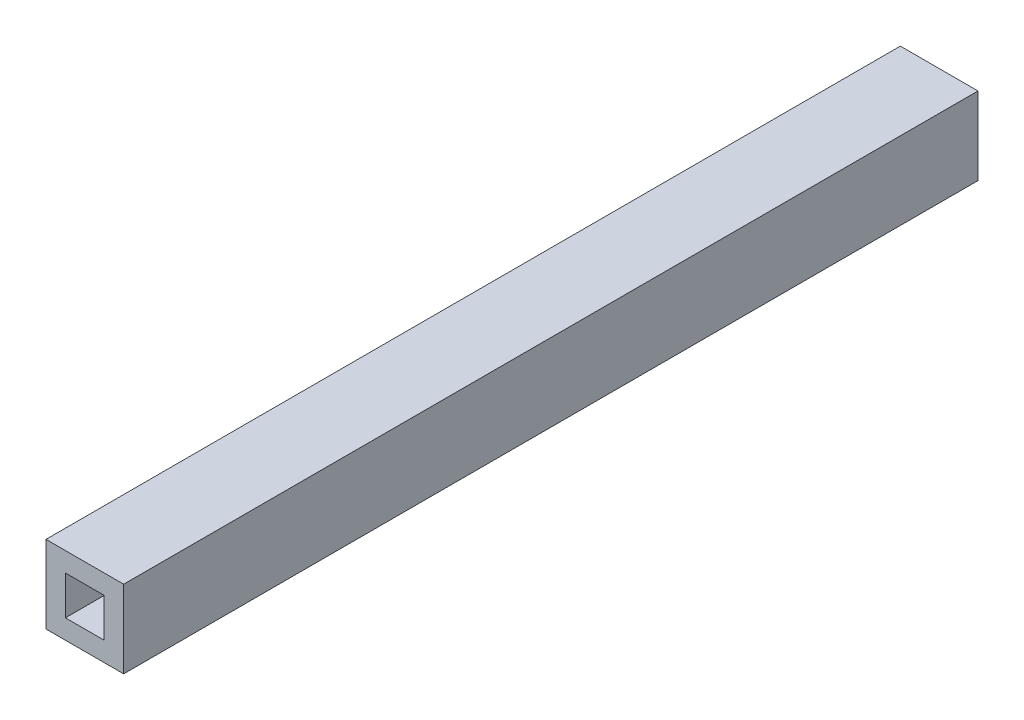
SolidWorks part; units mm, degrees
material "6063-O"
ref_plane "Front Plane" through (0, 0, 0) normal (0, 0, 1) x (1, 0, 0)
ref_plane "Top Plane" through (0, 0, 0) normal (0, 1, 0) x (1, 0, 0)
ref_plane "Right Plane" through (0, 0, 0) normal (1, 0, 0) x (0, 0, -1)
sketch "Sketch1" plane through (0, 0, 0) normal (0, 0, 1) x (1, 0, 0)
  line L1 (-10, -10) -> (10, -10)
  line L2 (-10, -10) -> (-10, 10)
  line L3 (-10, 10) -> (10, 10)
  line L4 (10, -10) -> (10, 10)
  line L5 (-10, -10) -> (10, 10) construction
  line L6 (-10, 10) -> (10, -10) construction
  point P0 (0, 0)
  dimension "D1" = 20
extrude "Extrude-Thin1" add sketch "Sketch1" along normal blind 220 thin thin type one direction reverse wall 5
